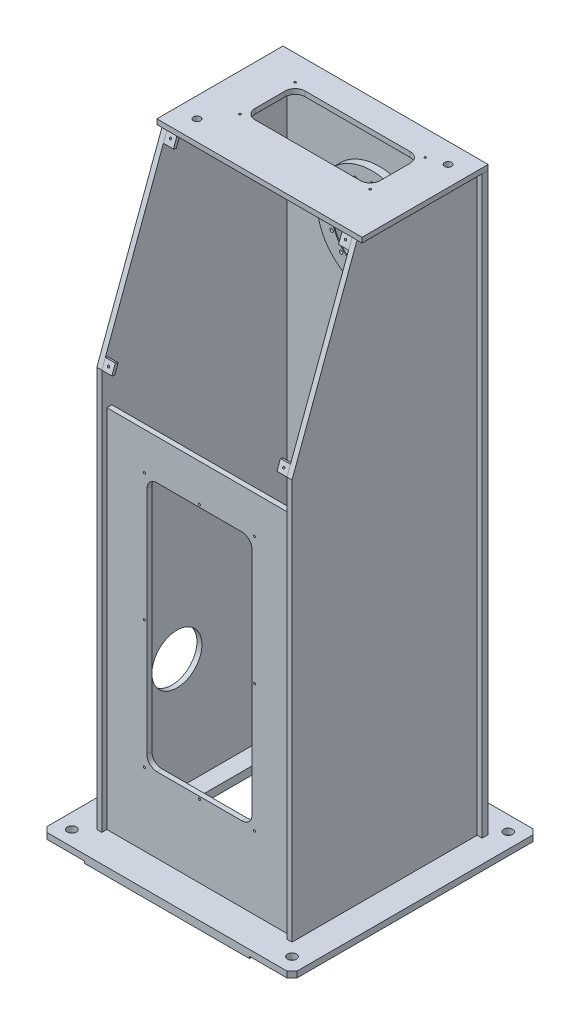
SolidWorks part; units mm, degrees
material "Q235"
ref_plane "前视基准面" through (0, 0, 0) normal (0, 0, 1) x (1, 0, 0)
ref_plane "上视基准面" through (0, 0, 0) normal (0, 1, 0) x (1, 0, 0)
ref_plane "右视基准面" through (0, 0, 0) normal (1, 0, 0) x (0, 0, -1)
sketch "草图1" plane through (0, 0, 0) normal (0, 0, 1) x (1, 0, 0)
  line L1 (-205, 575) -> (205, 575)
  line L2 (-205, 575) -> (-205, -575)
  line L3 (-205, -575) -> (205, -575)
  line L4 (205, 575) -> (205, -575)
  line L5 (-205, 575) -> (205, -575) construction
  line L6 (-205, -575) -> (205, 575) construction
  point P0 (0, 0)
  dimension "D1" = 410
  dimension "D2" = 1150
extrude "凸台-拉伸1" add sketch "草图1" along normal blind 12
sketch "草图2" plane through (0, 0, 12) normal (0, 0, 1) x (1, 0, 0)
  line L0 (55, 0) -> (-55, 0) construction
  line L1 (195, -575) -> (185, -575)
  line L2 (195, -575) -> (195, 575)
  line L3 (195, 575) -> (185, 575)
  line L4 (185, -575) -> (185, 575)
  line L5 (195, -575) -> (185, 575) construction
  line L6 (195, 575) -> (185, -575) construction
  line L7 (205, 575) -> (-205, 575) construction
  line L9 (-195, 575) -> (-185, 575)
  line L10 (-195, 575) -> (-195, -575)
  line L11 (-195, -575) -> (-185, -575)
  line L12 (-185, 575) -> (-185, -575)
  line L13 (-195, 575) -> (-185, -575) construction
  line L14 (-195, -575) -> (-185, 575) construction
  line L15 (205, -575) -> (205, 575) construction
  line L16 (-205, 575) -> (-205, -575) construction
  point P0 (190, 0)
  point P9 (-190, 0)
  dimension "D1" = 10
  dimension "D2" = 10
  dimension "D3" = 10
  dimension "D4" = 10
extrude "凸台-拉伸2" add sketch "草图2" along normal blind 370 separate body
sketch "草图3" plane through (0, 0, 0) normal (0, 0, -1) x (-1, 0, 0)
  line L0 (0, 55) -> (0, -55) construction
  line L1 (205, -575) -> (-205, -575) construction
  circle A0 centre (0, 375) radius 110
  dimension "D1" = 220
  dimension "D2" = 950
extrude "切除-拉伸1" cut sketch "草图3" against normal blind 400
sketch "草图4" plane through (0, 0, 12) normal (0, 0, 1) x (1, 0, 0)
  circle A0 centre (0, 375) radius 110
  circle A1 centre (0, 375) radius 80
  dimension "D1" = 160
  dimension "D2" = 220
extrude "凸台-拉伸3" add sketch "草图4" along normal blind 15 and the other way up to surface (12 mm away) separate body other way up to face at (-110, 375, 0)
sketch "草图5" plane through (0, 0, 27) normal (0, 0, 1) x (1, 0, 0)
  line L0 (0, 375) -> (0, 462.5) construction
  circle A0 centre (0, 375) radius 87.5 construction
  dimension "D1" = 175
hole_wizard "M8 螺纹孔1" positions "3D草图1" profile "草图7" tap size "M8" standard "Gb" end condition through all
sketch3d "3D草图1"
  point P0 (0, 462.5, 27)
sketch "草图7" plane through (0, 462.5, 27) normal (1, 0, 0) x (0, -1, 0)
  line L0 (0, 0) -> (0, 27)
  line L1 (0, 27) -> (3.4, 27)
  line L2 (3.4, 27) -> (3.4, 0)
  line L5 (3.4, 0) -> (0, 0)
  line L11 (0, -6.35) -> (0, 107.95) construction
  dimension "通孔螺纹孔钻头直径" = 6.8
  dimension "通孔螺纹孔钻头深度" = 27
cosmetic thread "孔螺蚊线1" parameters "D2"=8
pattern_circular "阵列(圆周)1" count 16 over 360 about axis through (0, 375, 0) along (0, 0, 1) of "M8 螺纹孔1"
sketch "草图9" plane through (0, -575, 0) normal (0, -1, 0) x (1, 0, 0)
  line L0 (0, -6.6) -> (0, 6.6) construction
  line L1 (250, -55) -> (-250, -55)
  line L2 (250, -55) -> (250, 437)
  line L3 (250, 437) -> (-250, 437)
  line L4 (-250, -55) -> (-250, 437)
  line L5 (250, -55) -> (-250, 437) construction
  line L6 (250, 437) -> (-250, -55) construction
  line L7 (225.5, 0) -> (-225.5, 0) construction
  line L10 (-195, 382) -> (-185, 382) construction
  point P0 (0, 191)
  dimension "D1" = 500
  dimension "D2" = 55
  dimension "D3" = 55
extrude "凸台-拉伸4" add sketch "草图9" along normal blind 16 separate body
sketch "草图10" plane through (0, -591, 0) normal (0, -1, 0) x (1, 0, 0)
  line L0 (0, -6.6) -> (0, 6.6) construction
  line L1 (-150, 331) -> (150, 331)
  line L2 (-150, 331) -> (-150, 81)
  line L3 (-150, 81) -> (150, 81)
  line L4 (150, 331) -> (150, 81)
  line L5 (-150, 331) -> (150, 81) construction
  line L6 (-150, 81) -> (150, 331) construction
  point P0 (0, 206)
  dimension "D1" = 300
  dimension "D2" = 250
extrude "切除-拉伸2" cut sketch "草图10" against normal blind 16
chamfer "倒角1" distance 10 angle 45 4 edges at (-250, -583, 437) (-250, -583, -55) (250, -583, -55) (250, -583, 437)
fillet "圆角1" radius 20 4 edges at (150, -583, 331) (150, -583, 81) (-150, -583, 81) (-150, -583, 331)
sketch "草图11" plane through (0, -575, 0) normal (0, 1, 0) x (1, 0, 0)
  line L0 (-205, -12) -> (205, -12) construction
  line L1 (-70, -81) -> (-78, -81)
  line L2 (-70, -81) -> (-70, -12)
  line L3 (-70, -12) -> (-78, -12)
  line L4 (-78, -81) -> (-78, -12)
  line L5 (-70, -81) -> (-78, -12) construction
  line L6 (-70, -12) -> (-78, -81) construction
  line L7 (78, -81) -> (70, -81)
  line L8 (78, -81) -> (78, -12)
  line L9 (78, -12) -> (70, -12)
  line L10 (70, -81) -> (70, -12)
  line L11 (78, -81) -> (70, -12) construction
  line L12 (78, -12) -> (70, -81) construction
  line L13 (-130, -81) -> (130, -81) construction
  point P0 (-74, -46.5)
  point P5 (74, -46.5)
  point P10 (0, -12)
  dimension "D1" = 8
  dimension "D2" = 70
  dimension "D3" = 8
  dimension "D4" = 140
  dimension "D5" = 0
  dimension "D6" = 0
  dimension "D7" = 0
extrude "凸台-拉伸5" add sketch "草图11" along normal blind 150 separate body
sketch "草图12" plane through (78, 0, 0) normal (1, 0, 0) x (0, 0, -1)
  line L0 (-12, -575) -> (-12, -495)
  line L1 (-12, 575) -> (-12, -575) construction
  line L2 (-12, -575) -> (-17, -575)
  line L3 (-81, -575) -> (-12, -575) construction
  line L4 (-17, -575) -> (-12, -495)
  line L7 (-81, -425) -> (-81, -575) construction
  line L8 (-81, -480) -> (-31, -425)
  line L9 (-81, -425) -> (-12, -425) construction
  line L10 (-31, -425) -> (-81, -425)
  line L11 (-81, -425) -> (-81, -480)
  dimension "D1" = 50
extrude "切除-拉伸3" cut sketch "草图12" against normal up to surface (156 mm away)
sketch "草图13" plane through (195, 0, 0) normal (1, 0, 0) x (0, 0, -1)
  line L0 (-252, 575) -> (-382, 575)
  line L2 (-382, 575) -> (-382, 225)
  line L3 (-382, -575) -> (-382, 575) construction
  line L4 (-382, 225) -> (-252, 575)
  dimension "D1" = 350
  dimension "D2" = 130
extrude "切除-拉伸4" cut sketch "草图13" against normal through all
sketch "草图14" plane through (0, -575, 0) normal (0, 1, 0) x (1, 0, 0)
  line L0 (0, -6.6) -> (0, 6.6) construction
  line L1 (185, -372) -> (-185, -372)
  line L2 (185, -372) -> (185, -362)
  line L3 (185, -362) -> (-185, -362)
  line L4 (-185, -372) -> (-185, -362)
  line L5 (185, -372) -> (-185, -362) construction
  line L6 (185, -362) -> (-185, -372) construction
  line L7 (-185, -252) -> (-185, -382) construction
  line L8 (185, -382) -> (185, -252) construction
  line L9 (-195, -382) -> (-185, -382) construction
  point P0 (0, -367)
  dimension "D1" = 10
  dimension "D2" = 10
extrude "凸台-拉伸6" add sketch "草图14" along normal blind 730 separate body
sketch "草图15" plane through (0, 575, 0) normal (0, 1, 0) x (1, 0, 0)
  line L0 (205, 0) -> (205, -252)
  line L3 (205, 0) -> (-205, 0) construction
  line L4 (205, -252) -> (-205, -252)
  line L5 (-205, -252) -> (-205, 0)
  line L6 (-205, 0) -> (205, 0)
  line L7 (205, -12) -> (205, 0) construction
  line L8 (-205, -12) -> (-205, 0) construction
  line L9 (185, -252) -> (195, -252) construction
extrude "凸台-拉伸7" add sketch "草图15" along normal blind 10 separate body
sketch "草图16" plane through (0, 0, 372) normal (0, 0, 1) x (1, 0, 0)
  line L0 (-185, 155) -> (185, 155) construction
  line L1 (-105, 75) -> (105, 75)
  line L2 (-105, 75) -> (-105, -425)
  line L3 (-105, -425) -> (105, -425)
  line L4 (105, 75) -> (105, -425)
  line L5 (-105, 75) -> (105, -425) construction
  line L6 (-105, -425) -> (105, 75) construction
  line L7 (-185, -575) -> (-185, 225) construction
  line L8 (185, 225) -> (185, -575) construction
  line L9 (-185, -575) -> (185, -575) construction
  point P0 (0, -175)
  dimension "D1" = 80
  dimension "D2" = 80
  dimension "D3" = 80
  dimension "D4" = 150
extrude "切除-拉伸5" cut sketch "草图16" against normal blind 10
chamfer "倒角3" distance 1 angle 45 1 edges at (80, 375, 27)
sketch "草图17" plane through (0, 585, 0) normal (0, 1, 0) x (1, 0, 0)
  line L1 (-125, -55.7403) -> (125, -55.7403)
  line L2 (-125, -55.7403) -> (-125, -155.7403)
  line L3 (-125, -155.7403) -> (125, -155.7403)
  line L4 (125, -55.7403) -> (125, -155.7403)
  line L5 (-125, -55.7403) -> (125, -155.7403) construction
  line L6 (-125, -155.7403) -> (125, -55.7403) construction
  point P0 (0, -105.7403)
  dimension "D1" = 250
  dimension "D2" = 100
  dimension "D3" = 0
extrude "切除-拉伸6" cut sketch "草图17" against normal blind 10
fillet "圆角2" radius 20 4 edges at (125, 580, 155.7403) (125, 580, 55.7403) (-125, 580, 155.7403) (-125, 580, 55.7403)
sketch "草图19" plane through (0, -575, 0) normal (0, 1, 0) x (1, 0, 0)
  line L0 (-110, -12) -> (110, -12) construction
  line L1 (-57.2592, 18.8981) -> (57.2592, 18.8981)
  line L2 (-57.2592, 18.8981) -> (-57.2592, -42.8981)
  line L3 (-57.2592, -42.8981) -> (57.2592, -42.8981)
  line L4 (57.2592, 18.8981) -> (57.2592, -42.8981)
  line L5 (-57.2592, 18.8981) -> (57.2592, -42.8981) construction
  line L6 (-57.2592, -42.8981) -> (57.2592, 18.8981) construction
  point P0 (0, -12)
split line "分割线5" [suppressed]
sketch "草图21" plane through (0, -575, 0) normal (0, 1, 0) x (1, 0, 0)
  line L0 (-250, -427) -> (-250, 45) construction
  line L1 (-240, 55) -> (240, 55) construction
  line L2 (250, 45) -> (250, -427) construction
  line L3 (240, -437) -> (-240, -437) construction
  circle A0 centre (-220, 25) radius 9
  circle A1 centre (-220, -407) radius 9
  circle A2 centre (220, -407) radius 9
  circle A3 centre (220, 25) radius 9
  dimension "D2" = 30
  dimension "D3" = 30
  dimension "D4" = 30
  dimension "D5" = 30
  dimension "D6" = 30
  dimension "D7" = 30
  dimension "D8" = 30
  dimension "D9" = 18
  dimension "D1" = 30
extrude "切除-拉伸8" cut sketch "草图21" against normal through all
hole_wizard "M5 螺纹孔1" positions "草图23" profile "草图22" tap size "M5" standard "GB"
sketch "草图23" plane through (0, 0, 372) normal (0, 0, 1) x (1, 0, 0)
  line L0 (105, 75) -> (-105, 75) construction
  line L1 (-105, 75) -> (-105, -425) construction
  line L2 (105, -425) -> (105, 75) construction
  line L3 (-105, -425) -> (105, -425) construction
  line L4 (-105, -425) -> (105, -425) construction
  point P0 (-110, 80)
  point P1 (-110, -175)
  point P3 (-110, -430)
  point P5 (0, -430)
  point P7 (110, -430)
  point P9 (110, -175)
  point P11 (110, 80)
  point P13 (0, 80)
  point P24 (-105, -175)
  point P27 (0, -425)
  point P30 (105, -175)
  dimension "D1" = 5
  dimension "D2" = 5
  dimension "D3" = 5
  dimension "D4" = 5
  dimension "D5" = 5
  dimension "D6" = 5
  dimension "D7" = 0
  dimension "D8" = 5
  dimension "D9" = 5
  dimension "D10" = 5
  dimension "D11" = 5
  dimension "D12" = 5
  dimension "D13" = 5
  dimension "D14" = 0
sketch "草图22" plane through (-110, 80, 372) normal (1, 0, 0) x (0, -1, 0)
  line L0 (0, 0) -> (0, 13.6618)
  line L1 (0, 13.6618) -> (2.1, 12.4)
  line L2 (2.1, 12.4) -> (2.1, 0)
  line L5 (2.1, 0) -> (0, 0)
  line L10 (0, 13.6618) -> (-2.1, 12.4) construction
  line L11 (0, -6.35) -> (0, 107.95) construction
  dimension "螺纹孔钻头直径" = 4.2
  dimension "螺纹孔钻头深度" = 12.4
  dimension "导头角度" = 118
cosmetic thread "孔螺蚊线2" parameters "D1"=10, "D2"=5
cosmetic thread "孔螺蚊线3" parameters "D1"=10, "D2"=5
cosmetic thread "孔螺蚊线4" parameters "D1"=10, "D2"=5
cosmetic thread "孔螺蚊线5" parameters "D1"=10, "D2"=5
cosmetic thread "孔螺蚊线7" parameters "D1"=10, "D2"=5
cosmetic thread "孔螺蚊线8" parameters "D1"=10, "D2"=5
cosmetic thread "孔螺蚊线9" parameters "D1"=10, "D2"=5
cosmetic thread "孔螺蚊线24" parameters "D1"=10, "D2"=5
fillet "圆角3" radius 20 4 edges at (105, 75, 367) (105, -425, 367) (-105, -425, 367) (-105, 75, 367)
hole_wizard "M5 螺纹孔2" positions "草图25" profile "草图24" tap size "M5" standard "GB"
sketch "草图25" plane through (0, 585, 0) normal (0, 1, 0) x (-1, 0, 0)
  line L0 (-105, 55.7403) -> (105, 55.7403) construction
  line L2 (125, 75.7403) -> (125, 135.7403) construction
  line L3 (105, 155.7403) -> (-105, 155.7403) construction
  line L4 (-125, 135.7403) -> (-125, 75.7403) construction
  point P0 (130, 160.7403)
  point P1 (130, 50.7403)
  point P3 (-130, 50.7403)
  point P5 (-130, 160.7403)
  dimension "D1" = 5
  dimension "D2" = 5
  dimension "D3" = 5
  dimension "D4" = 5
  dimension "D5" = 5
  dimension "D6" = 5
  dimension "D7" = 5
  dimension "D8" = 5
sketch "草图24" plane through (-130, 585, 160.7403) normal (1, 0, 0) x (0, 0, 1)
  line L0 (0, 0) -> (0, 13.6618)
  line L1 (0, 13.6618) -> (2.1, 12.4)
  line L2 (2.1, 12.4) -> (2.1, 0)
  line L5 (2.1, 0) -> (0, 0)
  line L10 (0, 13.6618) -> (-2.1, 12.4) construction
  line L11 (0, -6.35) -> (0, 107.95) construction
  dimension "螺纹孔钻头直径" = 4.2
  dimension "螺纹孔钻头深度" = 12.4
  dimension "导头角度" = 118
cosmetic thread "孔螺蚊线10" parameters "D1"=10, "D2"=5
cosmetic thread "孔螺蚊线11" parameters "D1"=10, "D2"=5
cosmetic thread "孔螺蚊线12" parameters "D1"=10, "D2"=5
cosmetic thread "孔螺蚊线13" parameters "D1"=10, "D2"=5
hole_wizard "M16 螺纹孔1" positions "草图27" profile "草图26" tap size "M16" standard "GB"
sketch "草图27" plane through (0, 585, 0) normal (0, 1, 0) x (-1, 0, 0)
  line L0 (205, 252) -> (-205, 252) construction
  line L1 (205, 0) -> (205, 252) construction
  line L2 (-205, 252) -> (-205, 0) construction
  line L3 (-205, 0) -> (205, 0) construction
  point P0 (165, 212)
  point P1 (-165, 40)
  dimension "D1" = 40
  dimension "D2" = 40
  dimension "D3" = 40
  dimension "D4" = 40
sketch "草图26" plane through (-165, 585, 212) normal (1, 0, 0) x (0, 0, 1)
  line L0 (0, 0) -> (0, 42.206)
  line L1 (0, 42.206) -> (7, 38)
  line L2 (7, 38) -> (7, 0)
  line L5 (7, 0) -> (0, 0)
  line L10 (0, 42.206) -> (-7, 38) construction
  line L11 (0, -6.35) -> (0, 107.95) construction
  dimension "螺纹孔钻头直径" = 14
  dimension "螺纹孔钻头深度" = 38
  dimension "导头角度" = 118
cosmetic thread "孔螺蚊线14" parameters "D1"=10, "D2"=16
cosmetic thread "孔螺蚊线15" parameters "D1"=10, "D2"=16
sketch "草图31" plane through (0, 575, 0) normal (0, -1, 0) x (1, 0, 0)
  line L1 (-145, 227) -> (-185, 227)
  line L2 (-145, 227) -> (-145, 197)
  line L3 (-145, 197) -> (-185, 197)
  line L4 (-185, 227) -> (-185, 197)
  line L5 (-145, 227) -> (-185, 197) construction
  line L6 (-145, 197) -> (-185, 227) construction
  line L10 (155, 25) -> (195, 55) construction
  line L11 (155, 55) -> (195, 25) construction
  line L12 (195, 55) -> (195, 25)
  line L13 (155, 25) -> (195, 25)
  line L14 (155, 55) -> (155, 25)
  line L15 (155, 55) -> (195, 55)
  circle A0 centre (165, 40) radius 7 construction
  point P0 (-165, 212)
  point P15 (175, 192)
  dimension "D1" = 40
  dimension "D2" = 30
  dimension "D3" = 15
extrude "凸台-拉伸8" add sketch "草图31" along normal blind 10 separate body
hole_wizard "M16 螺纹孔3" positions "草图37" profile "草图36" tap size "M16" standard "GB"
sketch "草图37" plane through (0, 575, 0) normal (0, 1, 0) x (-1, 0, 0)
  circle A0 centre (-165, 40) radius 7 construction
  point P0 (-165, 38.4957)
  point P1 (165, 212)
  dimension "D1" = 0
sketch "草图36" plane through (165, 575, 38.4957) normal (1, 0, 0) x (0, 0, 1)
  line L0 (0, 0) -> (0, 42.206)
  line L1 (0, 42.206) -> (7, 38)
  line L2 (7, 38) -> (7, 0)
  line L5 (7, 0) -> (0, 0)
  line L10 (0, 42.206) -> (-7, 38) construction
  line L11 (0, -6.35) -> (0, 107.95) construction
  dimension "螺纹孔钻头直径" = 14
  dimension "螺纹孔钻头深度" = 38
  dimension "导头角度" = 118
cosmetic thread "孔螺蚊线18" parameters "D1"=10, "D2"=16
cosmetic thread "孔螺蚊线19" parameters "D1"=10, "D2"=16
sketch "草图41" plane through (-185, 0, 0) normal (1, 0, 0) x (0, 0, -1)
  circle A0 centre (-232, -350) radius 50
extrude "切除-拉伸10" cut sketch "草图41" against normal through all
sketch "草图40" plane through (0, -591, 0) normal (0, -1, 0) x (1, 0, 0)
  line L0 (240, 437) -> (-240, 437) construction
  line L1 (165, -55) -> (-165, -55)
  line L2 (165, -55) -> (165, 437)
  line L3 (165, 437) -> (-165, 437)
  line L4 (-165, -55) -> (-165, 437)
  line L5 (165, -55) -> (-165, 437) construction
  line L6 (165, 437) -> (-165, -55) construction
  line L9 (-250, 427) -> (-250, -45) construction
  point P0 (0, 191)
  dimension "D1" = 330
  dimension "D2" = 85
extrude "切除-拉伸9" cut sketch "草图40" against normal blind 4 flip side to cut
sketch "草图42" plane through (0, 151.962, 409.1284) normal (0, 0.3482, 0.9374) x (1, 0, 0)
  line L0 (-185, 451.2765) -> (-165, 451.2765)
  line L1 (-205, 451.2765) -> (205, 451.2765) construction
  line L2 (-165, 451.2765) -> (-165, 431.2765)
  line L3 (-165, 431.2765) -> (-185, 431.2765)
  line L4 (-185, 451.2765) -> (-185, 77.9134) construction
  line L5 (-185, 431.2765) -> (-185, 451.2765)
  line L6 (-185, 77.9134) -> (-185, 97.9134)
  line L7 (-185, 97.9134) -> (-165, 97.9134)
  line L8 (-165, 97.9134) -> (-165, 77.9134)
  line L9 (-165, 77.9134) -> (-185, 77.9134)
  line L10 (0, 309.3236) -> (0, 15.7755) construction
  line L11 (-185, 15.7755) -> (185, 15.7755) construction
  line L12 (165, 77.9134) -> (185, 77.9134)
  line L13 (165, 97.9134) -> (165, 77.9134)
  line L14 (185, 97.9134) -> (165, 97.9134)
  line L15 (185, 77.9134) -> (185, 97.9134)
  line L16 (185, 431.2765) -> (185, 451.2765)
  line L17 (165, 431.2765) -> (185, 431.2765)
  line L18 (165, 451.2765) -> (165, 431.2765)
  line L19 (185, 451.2765) -> (165, 451.2765)
  dimension "D1" = 20
  dimension "D2" = 20
  dimension "D3" = 20
  dimension "D4" = 20
extrude "凸台-拉伸9" add sketch "草图42" against normal blind 6 separate body
sketch "草图47" plane through (205, 0, 0) normal (1, 0, 0) x (0, 0, -1)
  line L0 (-252, 575) -> (-248.2857, 585)
  line L1 (-252, 585) -> (0, 585) construction
  line L2 (-248.2857, 585) -> (-252, 585)
  line L3 (-252, 585) -> (-252, 575)
  line L4 (-382, 225) -> (-252, 575) construction
extrude "切除-拉伸12" [suppressed] cut sketch "草图47" against normal through all
sketch "草图48" plane through (195, 0, 0) normal (1, 0, 0) x (0, 0, -1)
  line L0 (-382, 225) -> (-252, 575) construction
hole_wizard "M5 螺纹孔3" positions "草图50" profile "草图49" tap size "M5" standard "GB"
sketch "草图50" plane through (0, 151.962, 409.1284) normal (0, 0.3482, 0.9374) x (1, 0, 0)
  line L0 (0, 0) -> (0, 131.0156) construction
  line L1 (165, 77.9134) -> (185, 77.9134) construction
  point P0 (-175, 87.9134)
  point P2 (-175, 442.9134)
  point P4 (175, 442.9134)
  point P6 (175, 87.9134)
  dimension "D1" = 350
  dimension "D2" = 355
  dimension "D3" = 10
sketch "草图49" plane through (-175, 234.3743, 378.5181) normal (1, 0, 0) x (0, -0.9374, 0.3482)
  line L0 (0, 0) -> (0, 15.2618)
  line L1 (0, 15.2618) -> (2.1, 14)
  line L2 (2.1, 14) -> (2.1, 0)
  line L5 (2.1, 0) -> (0, 0)
  line L10 (0, 15.2618) -> (-2.1, 14) construction
  line L11 (0, -6.35) -> (0, 107.95) construction
  dimension "螺纹孔钻头直径" = 4.2
  dimension "螺纹孔钻头深度" = 14
  dimension "导头角度" = 118
cosmetic thread "孔螺蚊线20" parameters "D1"=6, "D2"=5
cosmetic thread "孔螺蚊线21" parameters "D1"=6, "D2"=5
cosmetic thread "孔螺蚊线22" parameters "D1"=6, "D2"=5
cosmetic thread "孔螺蚊线23" parameters "D1"=6, "D2"=5
